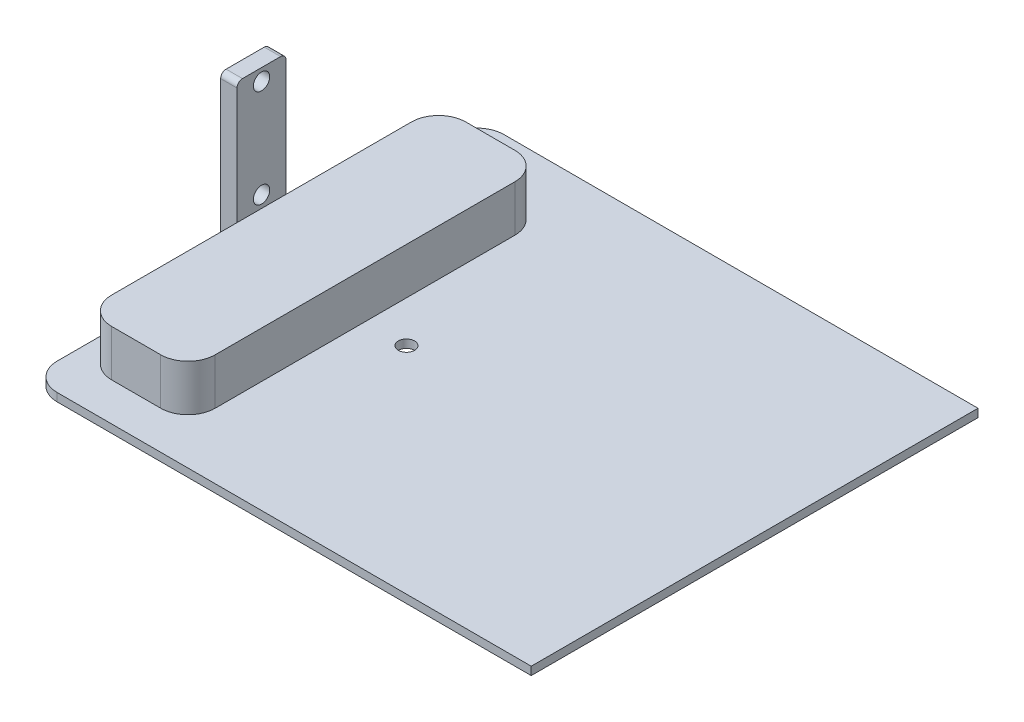
SolidWorks part; units mm, degrees
ref_plane "Plano frontal" through (0, 0, 0) normal (0, 0, 1) x (1, 0, 0)
ref_plane "Plano superior" through (0, 0, 0) normal (0, 1, 0) x (1, 0, 0)
ref_plane "Plano direito" through (0, 0, 0) normal (1, 0, 0) x (0, 0, -1)
sketch "Esboço1" plane through (0, 0, 0) normal (0, 1, 0) x (1, 0, 0)
  line L1 (-46, 41) -> (46, 41)
  line L2 (-46, 41) -> (-46, -41)
  line L3 (-46, -41) -> (46, -41)
  line L4 (46, 41) -> (46, -41)
  line L5 (-46, 41) -> (46, -41) construction
  line L6 (-46, -41) -> (46, 41) construction
  point P0 (0, 0)
  dimension "D1" = 92
  dimension "D2" = 82
extrude "Ressalto-extrusão1" add sketch "Esboço1" along normal blind 1.5
sketch "Esboço2" plane through (0, 1.5, 0) normal (0, 1, 0) x (1, 0, 0)
  line L1 (-43, 31) -> (-24, 31)
  line L2 (-43, 31) -> (-43, -34)
  line L3 (-43, -34) -> (-24, -34)
  line L4 (-24, 31) -> (-24, -34)
  line L6 (46, 41) -> (-46, 41) construction
  line L7 (-46, 41) -> (-46, -41) construction
  dimension "D1" = 19
  dimension "D2" = 65
  dimension "D3" = 10
  dimension "D4" = 3
extrude "Ressalto-extrusão2" add sketch "Esboço2" along normal blind 8.5
sketch "Esboço3" plane through (0, 1.5, 0) normal (0, 1, 0) x (1, 0, 0)
  line L0 (-46, 41) -> (-46, -41) construction
  line L1 (-46, -6) -> (-43, -6)
  line L2 (-46, -6) -> (-46, 3)
  line L3 (-46, 3) -> (-43, 3)
  line L4 (-43, -6) -> (-43, 3)
  line L5 (-43, 31) -> (-43, -34) construction
  line L6 (-43, -6) -> (-24, -6) construction
  line L7 (-24, -34) -> (-24, 31) construction
  line L8 (-43, 3) -> (-24, 3) construction
  line L13 (-24, -34) -> (-24, 31) construction
  line L14 (-33.5, 3) -> (-33.5, -6) construction
  line L19 (-43, 31) -> (-24, -34) construction
  line L20 (-33.5, -1.5) -> (-24, -1.5) construction
  line L21 (-43, -1.5) -> (-25, -1.5) construction
  dimension "D1" = 0
  dimension "D2" = 9
extrude "Ressalto-extrusão3" add sketch "Esboço3" along normal blind 30.9
sketch "Esboço4" plane through (-46, 0, 0) normal (1, 0, 0) x (0, 0, -1)
  line L0 (-6, 32.4) -> (3, 32.4) construction
  line L3 (-1.5, 10) -> (-1.5, 32.4) construction
  line L5 (-1.5, 21.2) -> (3, 21.2) construction
  line L7 (3, 32.4) -> (3, 10) construction
  circle A0 centre (-1.5, 30.2) radius 1.5
  circle A1 centre (-1.5, 12.2) radius 1.5
  point P0 (-1.5, 35.4)
  point P15 (3.8616, 24.2)
  point P20 (-6.736, 13)
  dimension "D1" = 18
  dimension "D2" = 3
extrude "Corte-extrusão1" cut sketch "Esboço4" along normal up to surface (3 mm away) up to face at (-43, 21.2, 1.5)
sketch "Esboço5" plane through (0, 1.5, 0) normal (0, 1, 0) x (1, 0, 0)
  line L0 (-46, -1.5) -> (-24, -1.5) construction
  line L1 (-46, 3) -> (-46, -6) construction
  line L2 (-24, -34) -> (-24, 31) construction
  line L3 (-24, -1.5) -> (-16.4, -1.5) construction
  circle A0 centre (-16.4, -1.5) radius 1.5
  dimension "D1" = 3
  dimension "D2" = 7.6
extrude "Corte-extrusão2" cut sketch "Esboço5" against normal up to surface (1.5 mm away) up to face at (0, 0, 0)
fillet "Filete1" radius 5 8 edges at (-44.5, 1.5, -3) (-44.5, 1.5, 6) (-24, 5.75, 34) (-43, 5.75, 34) (-24, 5.75, -31) (-43, 5.75, -31) (-46, 0.75, -41) (-46, 0.75, 41)
fillet "Filete2" radius 1 2 edges at (-44.5, 32.4, 6) (-44.5, 32.4, -3)
